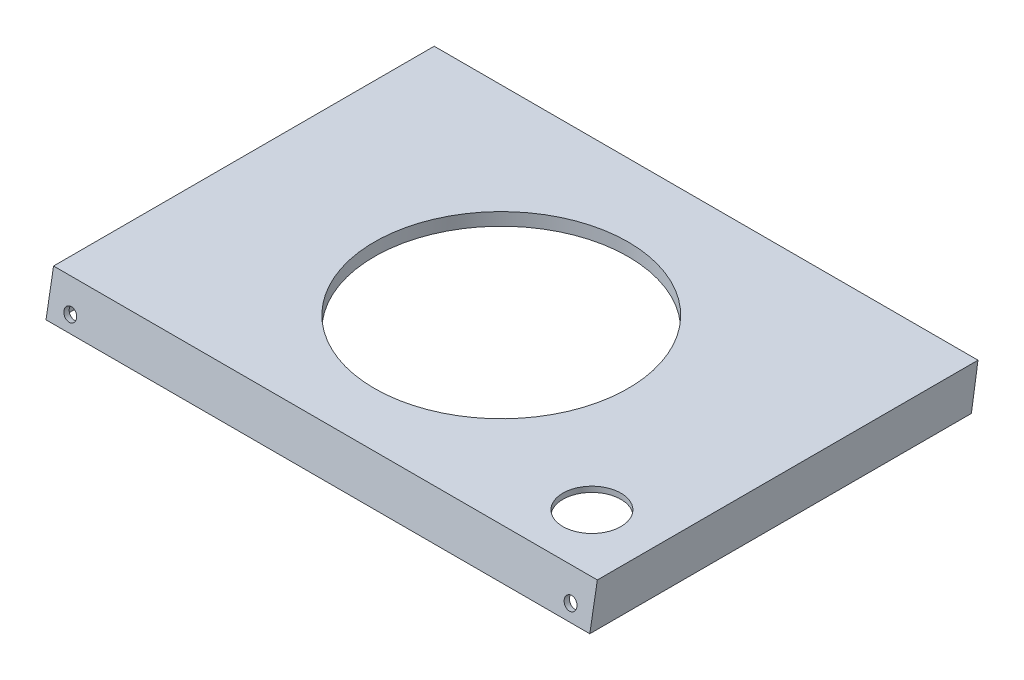
SolidWorks part; units mm, degrees
material "PE 低/中密度"
ref_plane "前视基准面" through (0, 0, 0) normal (0, 0, 1) x (1, 0, 0)
ref_plane "上视基准面" through (0, 0, 0) normal (0, 1, 0) x (1, 0, 0)
ref_plane "右视基准面" through (0, 0, 0) normal (1, 0, 0) x (0, 0, -1)
sketch "草图1" plane through (0, 0, 0) normal (0, 1, 0) x (1, 0, 0)
  line L0 (72, 0) -> (72, 105) construction
  line L1 (0, 0) -> (147, 0)
  line L2 (0, 0) -> (0, 105)
  line L3 (0, 105) -> (147, 105)
  line L4 (147, 0) -> (147, 105)
  circle A0 centre (72, 50) radius 35
  circle A1 centre (131, 16) radius 8
  dimension "D3" = 70
  dimension "D6" = 16
  dimension "D7" = 16
  dimension "D8" = 16
  dimension "D1" = 147
  dimension "D2" = 105
  dimension "D4" = 50
  dimension "D5" = 75
extrude "凸台-拉伸1" add sketch "草图1" along normal blind 1.5
sketch "草图2" plane through (0, 0, 0) normal (-1, 0, 0) x (0, 0, 1)
  line L1 (0, 1.5) -> (2.0838, -10.3177)
  line L2 (2.0838, -10.3177) -> (0.5606, -10.3177)
  line L3 (0.5606, -10.3177) -> (-1.5231, 1.5)
  line L4 (-105, 1.5) -> (0, 1.5) construction
  line L5 (-1.5231, 1.5) -> (0, 1.5)
  line L6 (-105, 0) -> (-103.1807, -10.3177)
  line L7 (-103.1807, -10.3177) -> (-101.6576, -10.3177)
  line L8 (-101.6576, -10.3177) -> (-103.7414, 1.5)
  line L9 (-103.7414, 1.5) -> (-105, 0)
  line L10 (0, 1.5) -> (0, 0) construction
  dimension "D1" = 1.5
  dimension "D2" = 1.5
  dimension "D3" = 12
  dimension "D4" = 10
extrude "凸台-拉伸2" add sketch "草图2" against normal blind 147
sketch "草图3" plane through (147, 0, 0) normal (1, 0, 0) x (0, 0, -1)
  line L0 (-2.0838, -10.3177) -> (0, 1.5)
  line L1 (0, 1.5) -> (105, 1.5)
  line L2 (105, 1.5) -> (103.1807, -10.3177)
  line L3 (103.1807, -10.3177) -> (-2.0838, -10.3177)
extrude "凸台-拉伸3" add sketch "草图3" along normal blind 1.5
sketch "草图4" plane through (0, 0, 0) normal (-1, 0, 0) x (0, 0, 1)
  line L0 (-103.1807, -10.3177) -> (-105, 1.5)
  line L1 (-105, 1.5) -> (0, 1.5)
  line L2 (0, 1.5) -> (2.0838, -10.3177)
  line L3 (2.0838, -10.3177) -> (-103.1807, -10.3177)
extrude "凸台-拉伸4" add sketch "草图4" along normal blind 1.5
sketch "草图5" plane through (0, 0, 0) normal (0, -1, 0) x (1, 0, 0)
  line L0 (129, -119.0646) -> (129, 23.7174) construction
  line L1 (141.6653, -72.1576) -> (112.0221, -72.1576) construction
  line L3 (147, -101.6576) -> (0, -101.6576) construction
  line L4 (147, -1.2586) -> (147, -103.4769) construction
  circle A0 centre (141, -95.6576) radius 3
  circle A1 centre (141, -95.6576) radius 1.1
  circle A2 centre (117, -95.6576) radius 1.1
  circle A3 centre (117, -95.6576) radius 3
  circle A4 centre (117, -48.6576) radius 3
  circle A5 centre (117, -48.6576) radius 1.1
  circle A6 centre (141, -48.6576) radius 1.1
  circle A7 centre (141, -48.6576) radius 3
  dimension "D1" = 47
  dimension "D5" = 6
  dimension "D6" = 2.2
  dimension "D2" = 24
  dimension "D3" = 6
  dimension "D4" = 6
extrude "凸台-拉伸5" add sketch "草图5" along normal blind 5
sketch "草图6" plane through (0, -17.9561, -101.8339) normal (0, -0.1736, -0.9848) x (-1, 0, 0)
  line L0 (-73.5, 7.7562) -> (-73.5, 29.4646) construction
  line L1 (-147, 7.7562) -> (0, 7.7562) construction
  circle A0 centre (-142.5, 11.7562) radius 1.75
  circle A1 centre (-4.5, 11.7562) radius 1.75
  dimension "D1" = 3.5
  dimension "D2" = 138
  dimension "D3" = 4
extrude "切除-拉伸1" cut sketch "草图6" against normal up to next
sketch "草图7" plane through (0, 0.0452, 0.2565) normal (0, 0.1736, 0.9848) x (1, 0, 0)
  line L0 (73.5, -10.5228) -> (73.5, 10.8693) construction
  line L1 (148.5, -10.5228) -> (-1.5, -10.5228) construction
  circle A0 centre (4.5, -6.5228) radius 1.75
  circle A1 centre (142.5, -6.5228) radius 1.75
  dimension "D1" = 4
  dimension "D2" = 3.5
  dimension "D3" = 138
extrude "切除-拉伸2" cut sketch "草图7" against normal up to next
sketch "草图8" plane through (0, 0, 0) normal (0, -1, 0) x (1, 0, 0)
  circle A0 centre (72, -50) radius 35
  circle A1 centre (72, -50) radius 36.5
  circle A2 centre (72, -50) radius 35 construction
  dimension "D1" = 1.5
extrude "凸台-拉伸6" add sketch "草图8" along normal blind 2
